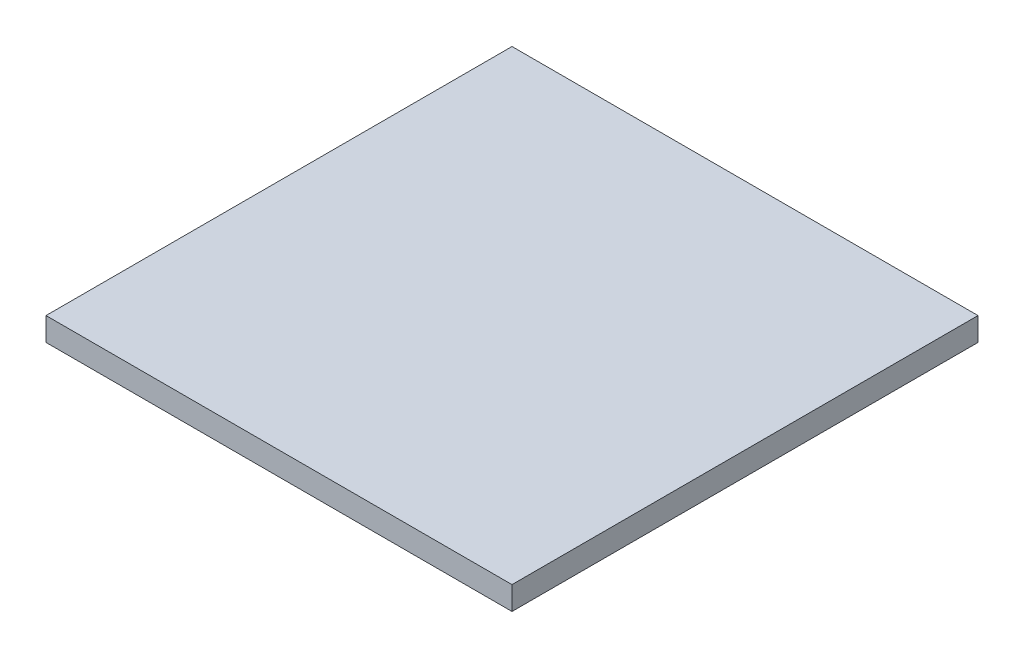
SolidWorks part; units mm, degrees
ref_plane "Front Plane" through (0, 0, 0) normal (0, 0, 1) x (1, 0, 0)
ref_plane "Top Plane" through (0, 0, 0) normal (0, 1, 0) x (1, 0, 0)
ref_plane "Right Plane" through (0, 0, 0) normal (1, 0, 0) x (0, 0, -1)
sketch "LED FOOTPRINT" plane through (0, 0, 0) normal (0, 1, 0) x (1, 0, 0)
  line L1 (0, 0) -> (80, 0) construction
  line L2 (0, 0) -> (0, -80) construction
  line L3 (0, -80) -> (80, -80) construction
  line L4 (80, 0) -> (80, -80) construction
sketch "PLUS CONTACTS" plane through (0, 0, 0) normal (0, 1, 0) x (1, 0, 0)
  line L0 (40, 0) -> (40, 5) construction
  line L1 (0, 0) -> (80, 0) construction
  line L2 (80, -39.0358) -> (85, -39.0358) construction
  line L3 (80, 0) -> (80, -80) construction
  line L4 (0, -40) -> (-5, -40) construction
  line L5 (0, 0) -> (0, -80) construction
  line L6 (40, -80) -> (40, -85) construction
  line L7 (0, -80) -> (80, -80) construction
  line L9 (-5, 5) -> (85, 5) construction
  line L10 (-5, 5) -> (-5, -85) construction
  line L11 (-5, -85) -> (85, -85) construction
  line L12 (85, 5) -> (85, -85) construction
sketch "LED OUTLINES" [suppressed] plane through (0, 0, 0) normal (0, 1, 0) x (1, 0, 0)
  line L0 (0, 0) -> (2.5, 0) construction
  line L1 (0, 0) -> (80, 0) construction
  line L2 (2.5, 0) -> (2.5, -2.5) construction
  line L3 (12.5, -2.5) -> (17.5, -2.5)
  line L4 (2.5, -2.5) -> (7.5, -2.5)
  line L5 (2.5, -2.5) -> (2.5, -7.5)
  line L6 (2.5, -7.5) -> (7.5, -7.5)
  line L7 (7.5, -2.5) -> (7.5, -7.5)
  line L8 (12.5, -2.5) -> (12.5, -7.5)
  line L9 (12.5, -7.5) -> (17.5, -7.5)
  line L10 (17.5, -2.5) -> (17.5, -7.5)
  line L11 (12.5, 0) -> (12.5, -2.5) construction
  line L12 (22.5, -2.5) -> (27.5, -2.5)
  line L13 (22.5, -2.5) -> (22.5, -7.5)
  line L14 (22.5, -7.5) -> (27.5, -7.5)
  line L15 (27.5, -2.5) -> (27.5, -7.5)
  line L16 (22.5, 0) -> (22.5, -2.5) construction
  line L17 (32.5, -2.5) -> (37.5, -2.5)
  line L18 (32.5, -2.5) -> (32.5, -7.5)
  line L19 (32.5, -7.5) -> (37.5, -7.5)
  line L20 (37.5, -2.5) -> (37.5, -7.5)
  line L21 (32.5, 0) -> (32.5, -2.5) construction
  line L22 (42.5, -2.5) -> (47.5, -2.5)
  line L23 (42.5, -2.5) -> (42.5, -7.5)
  line L24 (42.5, -7.5) -> (47.5, -7.5)
  line L25 (47.5, -2.5) -> (47.5, -7.5)
  line L26 (42.5, 0) -> (42.5, -2.5) construction
  line L27 (52.5, -2.5) -> (57.5, -2.5)
  line L28 (52.5, -2.5) -> (52.5, -7.5)
  line L29 (52.5, -7.5) -> (57.5, -7.5)
  line L30 (57.5, -2.5) -> (57.5, -7.5)
  line L31 (52.5, 0) -> (52.5, -2.5) construction
  line L32 (62.5, -2.5) -> (67.5, -2.5)
  line L33 (62.5, -2.5) -> (62.5, -7.5)
  line L34 (62.5, -7.5) -> (67.5, -7.5)
  line L35 (67.5, -2.5) -> (67.5, -7.5)
  line L36 (62.5, 0) -> (62.5, -2.5) construction
  line L37 (72.5, -2.5) -> (77.5, -2.5)
  line L38 (72.5, -2.5) -> (72.5, -7.5)
  line L39 (72.5, -7.5) -> (77.5, -7.5)
  line L40 (77.5, -2.5) -> (77.5, -7.5)
  line L41 (72.5, 0) -> (72.5, -2.5) construction
  line L42 (12.5, -12.5) -> (17.5, -12.5)
  line L43 (12.5, -12.5) -> (12.5, -17.5)
  line L44 (12.5, -17.5) -> (17.5, -17.5)
  line L45 (17.5, -12.5) -> (17.5, -17.5)
  line L46 (12.5, -10) -> (12.5, -12.5) construction
  line L47 (22.5, -12.5) -> (27.5, -12.5)
  line L48 (22.5, -12.5) -> (22.5, -17.5)
  line L49 (22.5, -17.5) -> (27.5, -17.5)
  line L50 (27.5, -12.5) -> (27.5, -17.5)
  line L51 (22.5, -10) -> (22.5, -12.5) construction
  line L52 (32.5, -12.5) -> (37.5, -12.5)
  line L53 (32.5, -12.5) -> (32.5, -17.5)
  line L54 (32.5, -17.5) -> (37.5, -17.5)
  line L55 (37.5, -12.5) -> (37.5, -17.5)
  line L56 (32.5, -10) -> (32.5, -12.5) construction
  line L57 (42.5, -12.5) -> (47.5, -12.5)
  line L58 (42.5, -12.5) -> (42.5, -17.5)
  line L59 (42.5, -17.5) -> (47.5, -17.5)
  line L60 (47.5, -12.5) -> (47.5, -17.5)
  line L61 (42.5, -10) -> (42.5, -12.5) construction
  line L62 (52.5, -12.5) -> (57.5, -12.5)
  line L63 (52.5, -12.5) -> (52.5, -17.5)
  line L64 (52.5, -17.5) -> (57.5, -17.5)
  line L65 (57.5, -12.5) -> (57.5, -17.5)
  line L66 (52.5, -10) -> (52.5, -12.5) construction
  line L67 (62.5, -12.5) -> (67.5, -12.5)
  line L68 (62.5, -12.5) -> (62.5, -17.5)
  line L69 (62.5, -17.5) -> (67.5, -17.5)
  line L70 (67.5, -12.5) -> (67.5, -17.5)
  line L71 (62.5, -10) -> (62.5, -12.5) construction
  line L72 (72.5, -12.5) -> (77.5, -12.5)
  line L73 (72.5, -12.5) -> (72.5, -17.5)
  line L74 (72.5, -17.5) -> (77.5, -17.5)
  line L75 (77.5, -12.5) -> (77.5, -17.5)
  line L76 (72.5, -10) -> (72.5, -12.5) construction
  line L77 (12.5, -22.5) -> (17.5, -22.5)
  line L78 (12.5, -22.5) -> (12.5, -27.5)
  line L79 (12.5, -27.5) -> (17.5, -27.5)
  line L80 (17.5, -22.5) -> (17.5, -27.5)
  line L81 (12.5, -20) -> (12.5, -22.5) construction
  line L82 (22.5, -22.5) -> (27.5, -22.5)
  line L83 (22.5, -22.5) -> (22.5, -27.5)
  line L84 (22.5, -27.5) -> (27.5, -27.5)
  line L85 (27.5, -22.5) -> (27.5, -27.5)
  line L86 (22.5, -20) -> (22.5, -22.5) construction
  line L87 (32.5, -22.5) -> (37.5, -22.5)
  line L88 (32.5, -22.5) -> (32.5, -27.5)
  line L89 (32.5, -27.5) -> (37.5, -27.5)
  line L90 (37.5, -22.5) -> (37.5, -27.5)
  line L91 (32.5, -20) -> (32.5, -22.5) construction
  line L92 (42.5, -22.5) -> (47.5, -22.5)
  line L93 (42.5, -22.5) -> (42.5, -27.5)
  line L94 (42.5, -27.5) -> (47.5, -27.5)
  line L95 (47.5, -22.5) -> (47.5, -27.5)
  line L96 (42.5, -20) -> (42.5, -22.5) construction
  line L97 (52.5, -22.5) -> (57.5, -22.5)
  line L98 (52.5, -22.5) -> (52.5, -27.5)
  line L99 (52.5, -27.5) -> (57.5, -27.5)
  line L100 (57.5, -22.5) -> (57.5, -27.5)
  line L101 (52.5, -20) -> (52.5, -22.5) construction
  line L102 (62.5, -22.5) -> (67.5, -22.5)
  line L103 (62.5, -22.5) -> (62.5, -27.5)
  line L104 (62.5, -27.5) -> (67.5, -27.5)
  line L105 (67.5, -22.5) -> (67.5, -27.5)
  line L106 (62.5, -20) -> (62.5, -22.5) construction
  line L107 (72.5, -22.5) -> (77.5, -22.5)
  line L108 (72.5, -22.5) -> (72.5, -27.5)
  line L109 (72.5, -27.5) -> (77.5, -27.5)
  line L110 (77.5, -22.5) -> (77.5, -27.5)
  line L111 (72.5, -20) -> (72.5, -22.5) construction
  line L112 (12.5, -32.5) -> (17.5, -32.5)
  line L113 (12.5, -32.5) -> (12.5, -37.5)
  line L114 (12.5, -37.5) -> (17.5, -37.5)
  line L115 (17.5, -32.5) -> (17.5, -37.5)
  line L116 (12.5, -30) -> (12.5, -32.5) construction
  line L117 (22.5, -32.5) -> (27.5, -32.5)
  line L118 (22.5, -32.5) -> (22.5, -37.5)
  line L119 (22.5, -37.5) -> (27.5, -37.5)
  line L120 (27.5, -32.5) -> (27.5, -37.5)
  line L121 (22.5, -30) -> (22.5, -32.5) construction
  line L122 (32.5, -32.5) -> (37.5, -32.5)
  line L123 (32.5, -32.5) -> (32.5, -37.5)
  line L124 (32.5, -37.5) -> (37.5, -37.5)
  line L125 (37.5, -32.5) -> (37.5, -37.5)
  line L126 (32.5, -30) -> (32.5, -32.5) construction
  line L127 (42.5, -32.5) -> (47.5, -32.5)
  line L128 (42.5, -32.5) -> (42.5, -37.5)
  line L129 (42.5, -37.5) -> (47.5, -37.5)
  line L130 (47.5, -32.5) -> (47.5, -37.5)
  line L131 (42.5, -30) -> (42.5, -32.5) construction
  line L132 (52.5, -32.5) -> (57.5, -32.5)
  line L133 (52.5, -32.5) -> (52.5, -37.5)
  line L134 (52.5, -37.5) -> (57.5, -37.5)
  line L135 (57.5, -32.5) -> (57.5, -37.5)
  line L136 (52.5, -30) -> (52.5, -32.5) construction
  line L137 (62.5, -32.5) -> (67.5, -32.5)
  line L138 (62.5, -32.5) -> (62.5, -37.5)
  line L139 (62.5, -37.5) -> (67.5, -37.5)
  line L140 (67.5, -32.5) -> (67.5, -37.5)
  line L141 (62.5, -30) -> (62.5, -32.5) construction
  line L142 (72.5, -32.5) -> (77.5, -32.5)
  line L143 (72.5, -32.5) -> (72.5, -37.5)
  line L144 (72.5, -37.5) -> (77.5, -37.5)
  line L145 (77.5, -32.5) -> (77.5, -37.5)
  line L146 (72.5, -30) -> (72.5, -32.5) construction
  line L147 (12.5, -42.5) -> (17.5, -42.5)
  line L148 (12.5, -42.5) -> (12.5, -47.5)
  line L149 (12.5, -47.5) -> (17.5, -47.5)
  line L150 (17.5, -42.5) -> (17.5, -47.5)
  line L151 (12.5, -40) -> (12.5, -42.5) construction
  line L152 (22.5, -42.5) -> (27.5, -42.5)
  line L153 (22.5, -42.5) -> (22.5, -47.5)
  line L154 (22.5, -47.5) -> (27.5, -47.5)
  line L155 (27.5, -42.5) -> (27.5, -47.5)
  line L156 (22.5, -40) -> (22.5, -42.5) construction
  line L157 (32.5, -42.5) -> (37.5, -42.5)
  line L158 (32.5, -42.5) -> (32.5, -47.5)
  line L159 (32.5, -47.5) -> (37.5, -47.5)
  line L160 (37.5, -42.5) -> (37.5, -47.5)
  line L161 (32.5, -40) -> (32.5, -42.5) construction
  line L162 (42.5, -42.5) -> (47.5, -42.5)
  line L163 (42.5, -42.5) -> (42.5, -47.5)
  line L164 (42.5, -47.5) -> (47.5, -47.5)
  line L165 (47.5, -42.5) -> (47.5, -47.5)
  line L166 (42.5, -40) -> (42.5, -42.5) construction
  line L167 (52.5, -42.5) -> (57.5, -42.5)
  line L168 (52.5, -42.5) -> (52.5, -47.5)
  line L169 (52.5, -47.5) -> (57.5, -47.5)
  line L170 (57.5, -42.5) -> (57.5, -47.5)
  line L171 (52.5, -40) -> (52.5, -42.5) construction
  line L172 (62.5, -42.5) -> (67.5, -42.5)
  line L173 (62.5, -42.5) -> (62.5, -47.5)
  line L174 (62.5, -47.5) -> (67.5, -47.5)
  line L175 (67.5, -42.5) -> (67.5, -47.5)
  line L176 (62.5, -40) -> (62.5, -42.5) construction
  line L177 (72.5, -42.5) -> (77.5, -42.5)
  line L178 (72.5, -42.5) -> (72.5, -47.5)
  line L179 (72.5, -47.5) -> (77.5, -47.5)
  line L180 (77.5, -42.5) -> (77.5, -47.5)
  line L181 (72.5, -40) -> (72.5, -42.5) construction
  line L182 (12.5, -52.5) -> (17.5, -52.5)
  line L183 (12.5, -52.5) -> (12.5, -57.5)
  line L184 (12.5, -57.5) -> (17.5, -57.5)
  line L185 (17.5, -52.5) -> (17.5, -57.5)
  line L186 (12.5, -50) -> (12.5, -52.5) construction
  line L187 (22.5, -52.5) -> (27.5, -52.5)
  line L188 (22.5, -52.5) -> (22.5, -57.5)
  line L189 (22.5, -57.5) -> (27.5, -57.5)
  line L190 (27.5, -52.5) -> (27.5, -57.5)
  line L191 (22.5, -50) -> (22.5, -52.5) construction
  line L192 (32.5, -52.5) -> (37.5, -52.5)
  line L193 (32.5, -52.5) -> (32.5, -57.5)
  line L194 (32.5, -57.5) -> (37.5, -57.5)
  line L195 (37.5, -52.5) -> (37.5, -57.5)
  line L196 (32.5, -50) -> (32.5, -52.5) construction
  line L197 (42.5, -52.5) -> (47.5, -52.5)
  line L198 (42.5, -52.5) -> (42.5, -57.5)
  line L199 (42.5, -57.5) -> (47.5, -57.5)
  line L200 (47.5, -52.5) -> (47.5, -57.5)
  line L201 (42.5, -50) -> (42.5, -52.5) construction
  line L202 (52.5, -52.5) -> (57.5, -52.5)
  line L203 (52.5, -52.5) -> (52.5, -57.5)
  line L204 (52.5, -57.5) -> (57.5, -57.5)
  line L205 (57.5, -52.5) -> (57.5, -57.5)
  line L206 (52.5, -50) -> (52.5, -52.5) construction
  line L207 (62.5, -52.5) -> (67.5, -52.5)
  line L208 (62.5, -52.5) -> (62.5, -57.5)
  line L209 (62.5, -57.5) -> (67.5, -57.5)
  line L210 (67.5, -52.5) -> (67.5, -57.5)
  line L211 (62.5, -50) -> (62.5, -52.5) construction
  line L212 (72.5, -52.5) -> (77.5, -52.5)
  line L213 (72.5, -52.5) -> (72.5, -57.5)
  line L214 (72.5, -57.5) -> (77.5, -57.5)
  line L215 (77.5, -52.5) -> (77.5, -57.5)
  line L216 (72.5, -50) -> (72.5, -52.5) construction
  line L217 (12.5, -62.5) -> (17.5, -62.5)
  line L218 (12.5, -62.5) -> (12.5, -67.5)
  line L219 (12.5, -67.5) -> (17.5, -67.5)
  line L220 (17.5, -62.5) -> (17.5, -67.5)
  line L221 (12.5, -60) -> (12.5, -62.5) construction
  line L222 (22.5, -62.5) -> (27.5, -62.5)
  line L223 (22.5, -62.5) -> (22.5, -67.5)
  line L224 (22.5, -67.5) -> (27.5, -67.5)
  line L225 (27.5, -62.5) -> (27.5, -67.5)
  line L226 (22.5, -60) -> (22.5, -62.5) construction
  line L227 (32.5, -62.5) -> (37.5, -62.5)
  line L228 (32.5, -62.5) -> (32.5, -67.5)
  line L229 (32.5, -67.5) -> (37.5, -67.5)
  line L230 (37.5, -62.5) -> (37.5, -67.5)
  line L231 (32.5, -60) -> (32.5, -62.5) construction
  line L232 (42.5, -62.5) -> (47.5, -62.5)
  line L233 (42.5, -62.5) -> (42.5, -67.5)
  line L234 (42.5, -67.5) -> (47.5, -67.5)
  line L235 (47.5, -62.5) -> (47.5, -67.5)
  line L236 (42.5, -60) -> (42.5, -62.5) construction
  line L237 (52.5, -62.5) -> (57.5, -62.5)
  line L238 (52.5, -62.5) -> (52.5, -67.5)
  line L239 (52.5, -67.5) -> (57.5, -67.5)
  line L240 (57.5, -62.5) -> (57.5, -67.5)
  line L241 (52.5, -60) -> (52.5, -62.5) construction
  line L242 (62.5, -62.5) -> (67.5, -62.5)
  line L243 (62.5, -62.5) -> (62.5, -67.5)
  line L244 (62.5, -67.5) -> (67.5, -67.5)
  line L245 (67.5, -62.5) -> (67.5, -67.5)
  line L246 (62.5, -60) -> (62.5, -62.5) construction
  line L247 (72.5, -62.5) -> (77.5, -62.5)
  line L248 (72.5, -62.5) -> (72.5, -67.5)
  line L249 (72.5, -67.5) -> (77.5, -67.5)
  line L250 (77.5, -62.5) -> (77.5, -67.5)
  line L251 (72.5, -60) -> (72.5, -62.5) construction
  line L252 (12.5, -72.5) -> (17.5, -72.5)
  line L253 (12.5, -72.5) -> (12.5, -77.5)
  line L254 (12.5, -77.5) -> (17.5, -77.5)
  line L255 (17.5, -72.5) -> (17.5, -77.5)
  line L256 (12.5, -70) -> (12.5, -72.5) construction
  line L257 (22.5, -72.5) -> (27.5, -72.5)
  line L258 (22.5, -72.5) -> (22.5, -77.5)
  line L259 (22.5, -77.5) -> (27.5, -77.5)
  line L260 (27.5, -72.5) -> (27.5, -77.5)
  line L261 (22.5, -70) -> (22.5, -72.5) construction
  line L262 (32.5, -72.5) -> (37.5, -72.5)
  line L263 (32.5, -72.5) -> (32.5, -77.5)
  line L264 (32.5, -77.5) -> (37.5, -77.5)
  line L265 (37.5, -72.5) -> (37.5, -77.5)
  line L266 (32.5, -70) -> (32.5, -72.5) construction
  line L267 (42.5, -72.5) -> (47.5, -72.5)
  line L268 (42.5, -72.5) -> (42.5, -77.5)
  line L269 (42.5, -77.5) -> (47.5, -77.5)
  line L270 (47.5, -72.5) -> (47.5, -77.5)
  line L271 (42.5, -70) -> (42.5, -72.5) construction
  line L272 (52.5, -72.5) -> (57.5, -72.5)
  line L273 (52.5, -72.5) -> (52.5, -77.5)
  line L274 (52.5, -77.5) -> (57.5, -77.5)
  line L275 (57.5, -72.5) -> (57.5, -77.5)
  line L276 (52.5, -70) -> (52.5, -72.5) construction
  line L277 (62.5, -72.5) -> (67.5, -72.5)
  line L278 (62.5, -72.5) -> (62.5, -77.5)
  line L279 (62.5, -77.5) -> (67.5, -77.5)
  line L280 (67.5, -72.5) -> (67.5, -77.5)
  line L281 (62.5, -70) -> (62.5, -72.5) construction
  line L282 (72.5, -72.5) -> (77.5, -72.5)
  line L283 (72.5, -72.5) -> (72.5, -77.5)
  line L284 (72.5, -77.5) -> (77.5, -77.5)
  line L285 (77.5, -72.5) -> (77.5, -77.5)
  line L286 (72.5, -70) -> (72.5, -72.5) construction
  line L287 (2.5, -12.5) -> (7.5, -12.5)
  line L288 (2.5, -12.5) -> (2.5, -17.5)
  line L289 (2.5, -17.5) -> (7.5, -17.5)
  line L290 (7.5, -12.5) -> (7.5, -17.5)
  line L291 (2.5, -10) -> (2.5, -12.5) construction
  line L292 (2.5, -22.5) -> (7.5, -22.5)
  line L293 (2.5, -22.5) -> (2.5, -27.5)
  line L294 (2.5, -27.5) -> (7.5, -27.5)
  line L295 (7.5, -22.5) -> (7.5, -27.5)
  line L296 (2.5, -20) -> (2.5, -22.5) construction
  line L297 (2.5, -32.5) -> (7.5, -32.5)
  line L298 (2.5, -32.5) -> (2.5, -37.5)
  line L299 (2.5, -37.5) -> (7.5, -37.5)
  line L300 (7.5, -32.5) -> (7.5, -37.5)
  line L301 (2.5, -30) -> (2.5, -32.5) construction
  line L302 (2.5, -42.5) -> (7.5, -42.5)
  line L303 (2.5, -42.5) -> (2.5, -47.5)
  line L304 (2.5, -47.5) -> (7.5, -47.5)
  line L305 (7.5, -42.5) -> (7.5, -47.5)
  line L306 (2.5, -40) -> (2.5, -42.5) construction
  line L307 (2.5, -52.5) -> (7.5, -52.5)
  line L308 (2.5, -52.5) -> (2.5, -57.5)
  line L309 (2.5, -57.5) -> (7.5, -57.5)
  line L310 (7.5, -52.5) -> (7.5, -57.5)
  line L311 (2.5, -50) -> (2.5, -52.5) construction
  line L312 (2.5, -62.5) -> (7.5, -62.5)
  line L313 (2.5, -62.5) -> (2.5, -67.5)
  line L314 (2.5, -67.5) -> (7.5, -67.5)
  line L315 (7.5, -62.5) -> (7.5, -67.5)
  line L316 (2.5, -60) -> (2.5, -62.5) construction
  line L317 (2.5, -72.5) -> (7.5, -72.5)
  line L318 (2.5, -72.5) -> (2.5, -77.5)
  line L319 (2.5, -77.5) -> (7.5, -77.5)
  line L320 (7.5, -72.5) -> (7.5, -77.5)
  line L321 (2.5, -70) -> (2.5, -72.5) construction
  dimension "D1" = 8
  dimension "D2" = 8
sketch "Outline" plane through (0, 0, 0) normal (0, 1, 0) x (1, 0, 0)
  line L0 (40, 5) -> (40, 10) construction
  line L1 (85, -39.0358) -> (90, -39.0358) construction
  line L2 (-5, -40) -> (-10, -40) construction
  line L3 (-5, 5) -> (-5, -85) construction
  line L4 (40, -85) -> (40, -90) construction
  line L6 (-10, 10) -> (90, 10)
  line L7 (-10, 10) -> (-10, -90)
  line L8 (-10, -90) -> (90, -90)
  line L9 (90, 10) -> (90, -90)
extrude "Boss-Extrude1" add sketch "Outline" along normal blind 4.5
sketch "Sketch3" plane through (0, 4.5, 0) normal (0, 1, 0) x (1, 0, 0)
  line L0 (80, -40) -> (85, -40) construction
  line L1 (80, 0) -> (80, -80) construction
  line L2 (0, -40) -> (-5, -40) construction
  line L3 (0, 0) -> (0, -80) construction
  line L4 (40, -80) -> (40, -85) construction
  line L5 (0, -80) -> (80, -80) construction
  line L6 (40, 0) -> (40, 5) construction
  line L7 (0, 0) -> (80, 0) construction
  line L9 (85, 5) -> (-5, 5)
  line L10 (85, 5) -> (85, -85)
  line L11 (85, -85) -> (-5, -85)
  line L12 (-5, 5) -> (-5, -85)
extrude "Cut-Extrude2" cut sketch "Sketch3" against normal through all flip side to cut
sketch "Sketch2" plane through (0, 4.5, 0) normal (0, 1, 0) x (1, 0, 0)
  line L0 (0, 0) -> (5, 0) construction
  line L1 (0, 0) -> (80, 0) construction
  line L2 (0, -40) -> (8.8043, -40) construction
  line L19 (5, 0) -> (10, 0) construction
  line L20 (5, 0) -> (5, 0.75) construction
  line L29 (5, -80.75) -> (1.6667, -80.75) construction
  line L30 (5, 0.75) -> (8.3333, 0.75) construction
  line L39 (5, 0.75) -> (1.6667, 0.75) construction
  line L40 (7.25, 1.5) -> (2.75, 1.5)
  line L41 (7.25, 1.5) -> (7.25, 0)
  line L42 (7.25, 0) -> (2.75, 0)
  line L43 (2.75, 1.5) -> (2.75, 0)
  line L44 (5, -80.75) -> (8.3333, -80.75) construction
  line L45 (5, -80) -> (5, -80.75) construction
  line L46 (5, -80) -> (10, -80) construction
  line L47 (0, -80) -> (5, -80) construction
  line L48 (2.75, -81.5) -> (2.75, -80)
  line L49 (7.25, -80) -> (2.75, -80)
  line L50 (7.25, -81.5) -> (7.25, -80)
  line L51 (7.25, -81.5) -> (2.75, -81.5)
  circle A0 centre (5, 0.75) radius 0.75 construction
  circle A1 centre (8.3333, 0.75) radius 0.75 construction
  circle A2 centre (1.6667, 0.75) radius 0.75 construction
  circle A6 centre (1.6667, -80.75) radius 0.75 construction
  circle A7 centre (8.3333, -80.75) radius 0.75 construction
  circle A8 centre (5, -80.75) radius 0.75 construction
